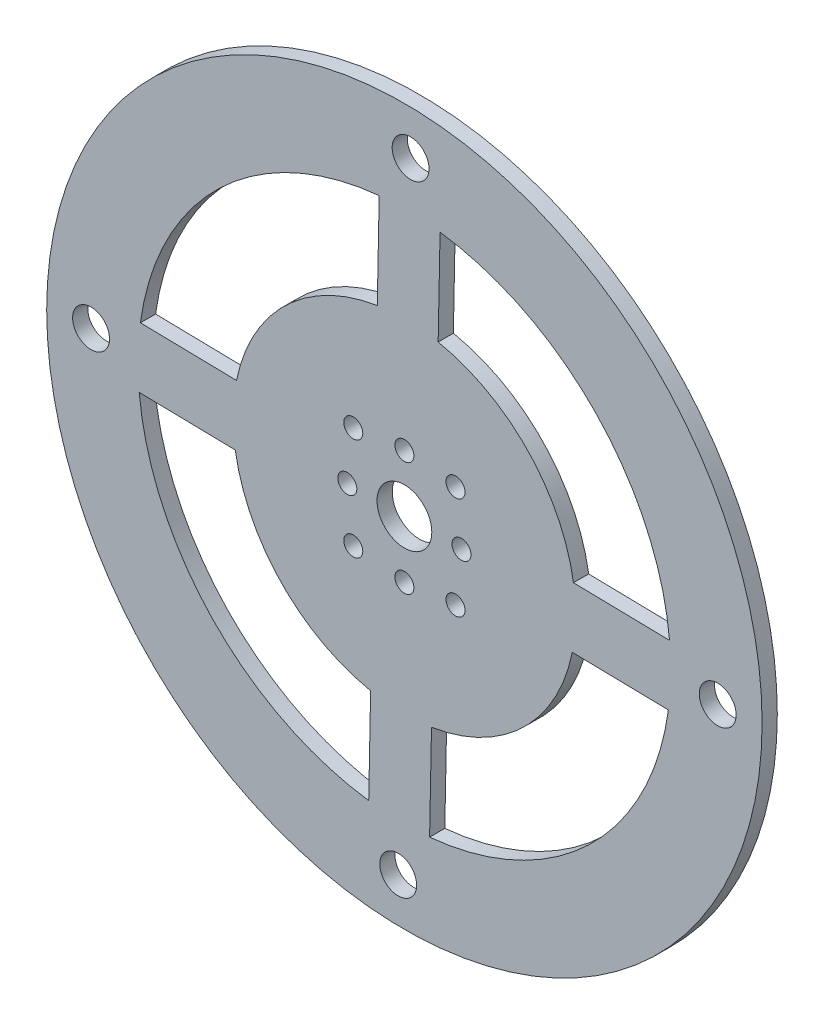
SolidWorks part; units mm, degrees
ref_plane "前视基准面" through (0, 0, 0) normal (0, 0, 1) x (1, 0, 0)
ref_plane "上视基准面" through (0, 0, 0) normal (0, 1, 0) x (1, 0, 0)
ref_plane "右视基准面" through (0, 0, 0) normal (1, 0, 0) x (0, 0, -1)
other "Configuration Table"
sketch "草图2" plane through (0, 0, 0) normal (0, 0, 1) x (1, 0, 0)
  line L0 (3.5617, -22.2163) -> (3.3122, -34.8429) construction
  line L1 (3.5617, -22.2163) -> (3.3122, -34.8429)
  line L2 (34.6848, -4.6863) -> (22.0582, -4.4367) construction
  line L3 (34.6848, -4.6863) -> (22.0582, -4.4367)
  line L4 (22.2163, 3.5617) -> (34.8429, 3.3122) construction
  line L5 (22.2163, 3.5617) -> (34.8429, 3.3122)
  line L6 (4.6863, 34.6848) -> (4.4367, 22.0582) construction
  line L7 (4.6863, 34.6848) -> (4.4367, 22.0582)
  line L8 (-3.5617, 22.2163) -> (-3.3122, 34.8429) construction
  line L9 (-3.5617, 22.2163) -> (-3.3122, 34.8429)
  line L10 (-34.6848, 4.6863) -> (-22.0582, 4.4367) construction
  line L11 (-34.6848, 4.6863) -> (-22.0582, 4.4367)
  line L12 (-22.2163, -3.5617) -> (-34.8429, -3.3122) construction
  line L13 (-22.2163, -3.5617) -> (-34.8429, -3.3122)
  line L14 (-4.6863, -34.6848) -> (-4.4367, -22.0582) construction
  line L15 (-29.6086, 89.0047) -> (-30.3717, 50.3923)
  line L16 (-28.1812, 90.3768) -> (-29.6086, 89.0047)
  line L17 (-23.3406, 90.2811) -> (-28.1812, 90.3768)
  line L18 (-19.4204, 86.2029) -> (-23.3406, 90.2811)
  line L19 (29.0516, 85.2449) -> (-19.4204, 86.2029)
  line L20 (33.1299, 89.1651) -> (29.0516, 85.2449)
  line L21 (37.2975, 89.0827) -> (33.1299, 89.1651)
  line L22 (38.6696, 87.6553) -> (37.2975, 89.0827)
  line L23 (38.0646, 57.0413) -> (38.6696, 87.6553)
  line L24 (32.3391, 49.1529) -> (38.0646, 57.0413)
  line L25 (59.8715, 3.9241) -> (32.3391, 49.1529)
  line L26 (23.8138, -60.2646) -> (59.6697, -6.2867)
  line L27 (-26.1764, -59.2766) -> (23.8138, -60.2646)
  line L28 (-59.8715, -3.9241) -> (-26.1764, -59.2766)
  line L29 (-30.3717, 50.3923) -> (-59.6697, 6.2867)
  line L30 (-29.6086, 89.0047) -> (-30.3717, 50.3923)
  line L31 (-28.1812, 90.3768) -> (-29.6086, 89.0047)
  line L32 (-23.3406, 90.2811) -> (-28.1812, 90.3768)
  line L33 (-19.4204, 86.2029) -> (-23.3406, 90.2811)
  line L34 (29.0516, 85.2449) -> (-19.4204, 86.2029)
  line L35 (33.1299, 89.1651) -> (29.0516, 85.2449)
  line L36 (37.2975, 89.0827) -> (33.1299, 89.1651)
  line L37 (38.6696, 87.6553) -> (37.2975, 89.0827)
  line L38 (38.0646, 57.0413) -> (38.6696, 87.6553)
  line L39 (32.3391, 49.1529) -> (38.0646, 57.0413)
  line L40 (59.8715, 3.9241) -> (32.3391, 49.1529)
  line L41 (23.8138, -60.2646) -> (59.6697, -6.2867)
  line L42 (-26.1764, -59.2766) -> (23.8138, -60.2646)
  line L43 (-59.8715, -3.9241) -> (-26.1764, -59.2766)
  line L44 (-30.3717, 50.3923) -> (-59.6697, 6.2867)
  line L45 (-4.6863, -34.6848) -> (-4.4367, -22.0582)
  circle A0 centre (6.7175, 6.7175) radius 1.25 construction
  circle A1 centre (0, 0) radius 22.5
  circle A2 centre (0, 0) radius 22.5
  circle A3 centre (6.7175, 6.7175) radius 1.25
  circle A4 centre (0, 7.5) radius 1.25 construction
  circle A5 centre (0, 7.5) radius 1.25
  circle A6 centre (-6.7175, 6.7175) radius 1.25 construction
  circle A7 centre (-6.7175, 6.7175) radius 1.25
  circle A8 centre (-7.5, 0) radius 1.25 construction
  circle A9 centre (-7.5, 0) radius 1.25
  circle A10 centre (-6.7175, -6.7175) radius 1.25 construction
  circle A11 centre (-6.7175, -6.7175) radius 1.25
  circle A12 centre (0, -7.5) radius 1.25 construction
  circle A13 centre (0, -7.5) radius 1.25
  circle A14 centre (6.7175, -6.7175) radius 1.25 construction
  circle A15 centre (6.7175, -6.7175) radius 1.25
  circle A16 centre (7.5, 0) radius 1.25 construction
  circle A17 centre (7.5, 0) radius 1.25
  circle A18 centre (0, 0) radius 3.6 construction
  circle A19 centre (0, 0) radius 3.6
  circle A20 centre (0, 0) radius 35 construction
  circle A21 centre (0, 0) radius 35
  circle A22 centre (-0.8136, -41.167) radius 2.425 construction
  circle A23 centre (-0.8136, -41.167) radius 2.425
  arc A24 (59.6697, -6.2867) -> (59.8715, 3.9241) centre (0, 0) ccw
  arc A25 (-59.6697, 6.2867) -> (-59.8715, -3.9241) centre (0, 0) ccw
  arc A26 (59.6697, -6.2867) -> (59.8715, 3.9241) centre (0, 0) ccw
  arc A27 (-59.6697, 6.2867) -> (-59.8715, -3.9241) centre (0, 0) ccw
  circle A28 centre (0.8136, 41.167) radius 2.425 construction
  circle A29 centre (0.8136, 41.167) radius 2.425
  circle A30 centre (41.167, -0.8136) radius 2.425 construction
  circle A31 centre (41.167, -0.8136) radius 2.425
  circle A32 centre (-41.167, 0.8136) radius 2.425 construction
  circle A33 centre (-41.167, 0.8136) radius 2.425
  circle A34 centre (0, 0) radius 47 construction
  circle A35 centre (0, 0) radius 47
  circle M22 centre (0, 0) radius 3.6
  circle M23 centre (7.5, 0) radius 1.25
  circle M24 centre (6.7175, 6.7175) radius 1.25
  circle M25 centre (0, 7.5) radius 1.25
  circle M26 centre (-7.5, 0) radius 1.25
  circle M27 centre (0, -7.5) radius 1.25
  circle M28 centre (6.7175, -6.7175) radius 1.25
  circle M29 centre (0, 0) radius 22.5
  circle M30 centre (-6.7175, -6.7175) radius 1.25
  circle M31 centre (-6.7175, 6.7175) radius 1.25
  dimension "D1" = 0
  dimension "D2" = 0
extrude "凸台-拉伸1" add sketch "草图2" along normal blind 2 contours M29 M23 M25 M27 M31 M30 M28 M26 M24 M22 | L7 A21 L9 M29 | L3 A21 L5 M29 | L45 A21 L1 M29 | L11 A21 L13 M29 | A35 A23 A21 A29 A31 A33
